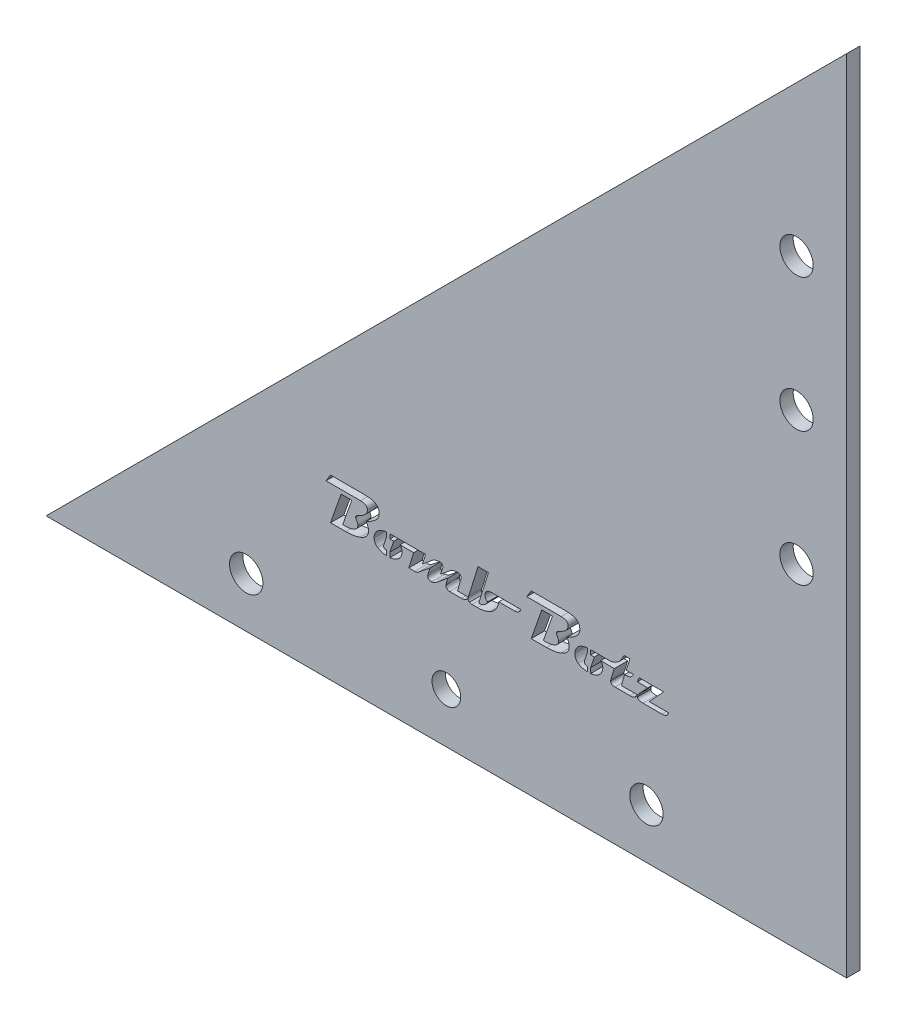
SolidWorks part; units mm, degrees
ref_plane "Front Plane" through (0, 0, 0) normal (0, 0, 1) x (1, 0, 0)
ref_plane "Top Plane" through (0, 0, 0) normal (0, 1, 0) x (1, 0, 0)
ref_plane "Right Plane" through (0, 0, 0) normal (1, 0, 0) x (0, 0, -1)
sketch "Sketch4" plane through (0, 0, 0) normal (0, 0, 1) x (1, 0, 0)
  line L0 (0, 0) -> (-152.4, 0)
  line L1 (0, 0) -> (0, 152.4)
  line L2 (-152.4, 0) -> (0, 152.4)
  dimension "D1" = 152.4
  dimension "D2" = 152.4
extrude "Boss-Extrude4" add sketch "Sketch4" along normal blind 2.54
sketch "Sketch5" plane through (0, 0, 2.54) normal (0, 0, 1) x (1, 0, 0)
  line L0 (-152.4, 0) -> (0, 0) construction
  line L1 (0, 0) -> (0, 152.4) construction
  circle A0 centre (-114.3, 9.525) radius 3.175
  circle A1 centre (-76.2, 9.525) radius 2.7305
  circle A2 centre (-38.1, 9.525) radius 3.175
  circle A3 centre (-9.525, 63.5) radius 3.175
  circle A4 centre (-9.525, 88.9) radius 3.175
  circle A5 centre (-9.525, 114.3) radius 3.175
  dimension "D1" = 6.35
  dimension "D2" = 9.525
  dimension "D3" = 5.461
  dimension "D4" = 6.35
  dimension "D5" = 6.35
  dimension "D6" = 6.35
  dimension "D7" = 6.35
  dimension "D8" = 9.525
  dimension "D9" = 9.525
  dimension "D10" = 38.1
  dimension "D11" = 76.2
  dimension "D12" = 114.3
  dimension "D13" = 63.5
  dimension "D14" = 9.525
  dimension "D15" = 88.9
  dimension "D16" = 9.525
  dimension "D17" = 114.3
  dimension "D18" = 9.525
extrude "Cut-Extrude1" cut sketch "Sketch5" against normal blind 2.54
sketch "Sketch6" plane through (0, 0, 2.54) normal (0, 0, 1) x (1, 0, 0)
  text T0 "Bomb Botz" font "Magneto" height in points 28
extrude "Cut-Extrude2" cut sketch "Sketch6" against normal blind 2.54
sketch "Sketch7" plane through (0, 0, 2.54) normal (0, 0, 1) x (1, 0, 0)
  line L1 (-87.5686, 30.4849) -> (-86.9494, 30.4849)
  line L2 (-87.5686, 30.4849) -> (-87.5686, 24.319)
  line L3 (-87.5686, 24.319) -> (-86.9494, 24.319)
  line L4 (-86.9494, 30.4849) -> (-86.9494, 24.319)
  line L5 (-49.3346, 30.4849) -> (-48.7154, 30.4849)
  line L6 (-49.3346, 30.4849) -> (-49.3346, 23.2458)
  line L7 (-49.3346, 23.2458) -> (-48.7154, 23.2458)
  line L8 (-48.7154, 30.4849) -> (-48.7154, 23.2458)
extrude "Boss-Extrude5" add sketch "Sketch7" against normal blind 2.54
